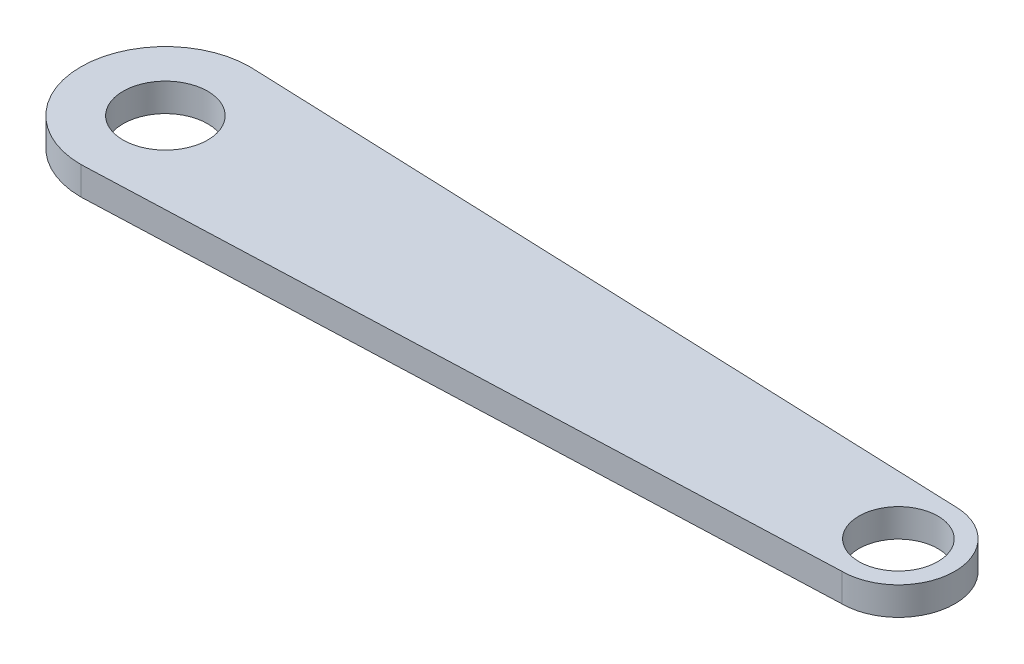
SolidWorks part; units mm, degrees
ref_plane "Front Plane" through (0, 0, 0) normal (0, 0, 1) x (1, 0, 0)
ref_plane "Top Plane" through (0, 0, 0) normal (0, 1, 0) x (1, 0, 0)
ref_plane "Right Plane" through (0, 0, 0) normal (1, 0, 0) x (0, 0, -1)
sketch "Sketch3" plane through (0, 0, 0) normal (0, 1, 0) x (1, 0, 0)
  line L0 (-115.5405, 0) -> (14.4595, 0) construction
  line L1 (-115.5405, 15) -> (14.4595, 10)
  line L2 (-115.5405, -15) -> (14.4595, -10)
  arc A0 (-115.5405, 15) -> (-115.5405, -15) centre (-115.5405, 0) ccw
  arc A1 (14.4595, -10) -> (14.4595, 10) centre (14.4595, 0) ccw
  dimension "D1" = 30
  dimension "D2" = 20
  dimension "D3" = 130
extrude "Boss-Extrude1" add sketch "Sketch3" along normal blind 5
sketch "Sketch4" plane through (0, 0, 0) normal (0, -1, 0) x (1, 0, 0)
  circle A0 centre (14.4595, 0) radius 7
  circle A1 centre (-115.5405, 0) radius 7.5
  dimension "D1" = 14
  dimension "D2" = 15
extrude "Cut-Extrude1" cut sketch "Sketch4" against normal blind 10
